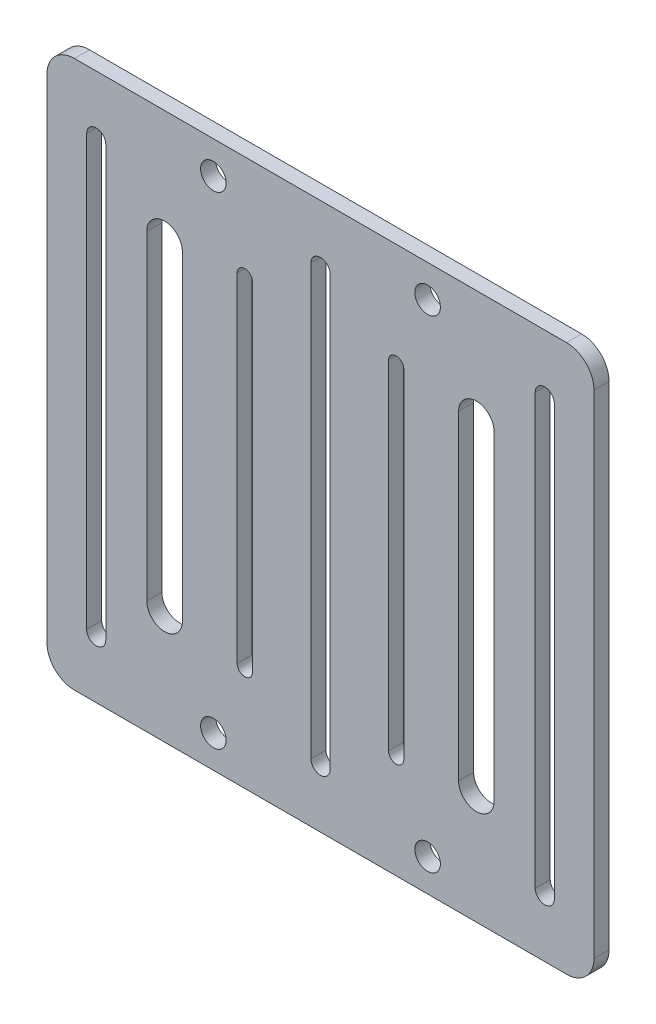
SolidWorks part; units mm, degrees
ref_plane "Front Plane" through (0, 0, 0) normal (0, 0, 1) x (1, 0, 0)
ref_plane "Top Plane" through (0, 0, 0) normal (0, 1, 0) x (1, 0, 0)
ref_plane "Right Plane" through (0, 0, 0) normal (1, 0, 0) x (0, 0, -1)
sketch "Sketch1" plane through (0, 0, 0) normal (0, 0, 1) x (1, 0, 0)
  line L1 (27, -30) -> (-27, -30)
  line L2 (30, -27) -> (30, 27)
  line L3 (27, 30) -> (-27, 30)
  line L4 (-30, -27) -> (-30, 27)
  line L5 (30, -30) -> (-30, 30) construction
  line L6 (30, 30) -> (-30, -30) construction
  arc A0 (30, 27) -> (27, 30) centre (27, 27) ccw
  arc A1 (30, -27) -> (27, -30) centre (27, -27) cw
  arc A2 (-27, -30) -> (-30, -27) centre (-27, -27) cw
  arc A3 (-30, 27) -> (-27, 30) centre (-27, 27) cw
  point P0 (0, 0)
  dimension "D3" = 3
  dimension "D1" = 60
  dimension "D2" = 60
extrude "Boss-Extrude1" add sketch "Sketch1" along normal blind 1.65
ref_plane "Plane1" through (0, 0, 1.65) normal (0, 0, 1) x (1, 0, 0)
sketch "Sketch2" plane through (0, 0, 1.65) normal (0, 0, 1) x (1, 0, 0)
  line L0 (23.5515, -23.55) -> (23.5515, 23.55)
  line L2 (-1.0485, -23.55) -> (-1.0485, 23.55)
  line L4 (1.0485, -23.55) -> (1.0485, 23.55)
  line L5 (25.6485, -23.55) -> (25.6485, 23.55)
  line L6 (-25.6485, -23.55) -> (-25.6485, 23.55)
  line L7 (-23.5515, -23.55) -> (-23.5515, 23.55)
  line L8 (0, 0) -> (-8.3, 0) construction
  line L9 (0, 0) -> (0, 24.5985) construction
  line L11 (-9.1388, -18.55) -> (-9.1388, 18.55)
  line L13 (-7.4612, -18.55) -> (-7.4612, 18.55)
  line L14 (-8.3, 0) -> (-17.1, 0) construction
  line L15 (15.15, -17.55) -> (15.15, 17.55)
  line L17 (-19.05, -17.55) -> (-19.05, 17.55)
  line L19 (-15.15, -17.55) -> (-15.15, 17.55)
  line L20 (19.05, -17.55) -> (19.05, 17.55)
  line L21 (7.4612, -18.55) -> (7.4612, 18.55)
  line L22 (9.1388, -18.55) -> (9.1388, 18.55)
  line L23 (0, 23.55) -> (0, 26.45) construction
  line L24 (0, 26.45) -> (-11.75, 26.45) construction
  arc A0 (1.0485, 23.55) -> (-1.0485, 23.55) centre (0, 23.55) ccw
  arc A1 (-1.0485, -23.55) -> (1.0485, -23.55) centre (0, -23.55) ccw
  arc A2 (25.6485, 23.55) -> (23.5515, 23.55) centre (24.6, 23.55) ccw
  arc A3 (23.5515, -23.55) -> (25.6485, -23.55) centre (24.6, -23.55) ccw
  arc A4 (-23.5515, 23.55) -> (-25.6485, 23.55) centre (-24.6, 23.55) ccw
  arc A5 (-25.6485, -23.55) -> (-23.5515, -23.55) centre (-24.6, -23.55) ccw
  arc A6 (-7.4612, 18.55) -> (-9.1388, 18.55) centre (-8.3, 18.55) ccw
  arc A7 (-9.1388, -18.55) -> (-7.4612, -18.55) centre (-8.3, -18.55) ccw
  arc A8 (-15.15, 17.55) -> (-19.05, 17.55) centre (-17.1, 17.55) ccw
  arc A9 (-19.05, -17.55) -> (-15.15, -17.55) centre (-17.1, -17.55) ccw
  arc A10 (19.05, -17.55) -> (15.15, -17.55) centre (17.1, -17.55) cw
  arc A11 (15.15, 17.55) -> (19.05, 17.55) centre (17.1, 17.55) cw
  arc A12 (9.1388, -18.55) -> (7.4612, -18.55) centre (8.3, -18.55) cw
  arc A13 (7.4612, 18.55) -> (9.1388, 18.55) centre (8.3, 18.55) cw
  circle A14 centre (-11.75, 26.45) radius 1.4
  circle A15 centre (11.75, 26.45) radius 1.4
  circle A16 centre (11.75, -26.45) radius 1.4
  circle A17 centre (-11.75, -26.45) radius 1.4
  point P0 (0, 0)
  dimension "D11" = 2.8
  dimension "D1" = 47.1
  dimension "D4" = 8.3
  dimension "D5" = 37.1
  dimension "D6" = 8.8
  dimension "D7" = 3.9
  dimension "D8" = 35.1
  dimension "D9" = 2.9
  dimension "D10" = 11.75
  dimension "D2" = 2
  dimension "D3" = 2
extrude "Cut-Extrude1" cut sketch "Sketch2" against normal blind 1.65
